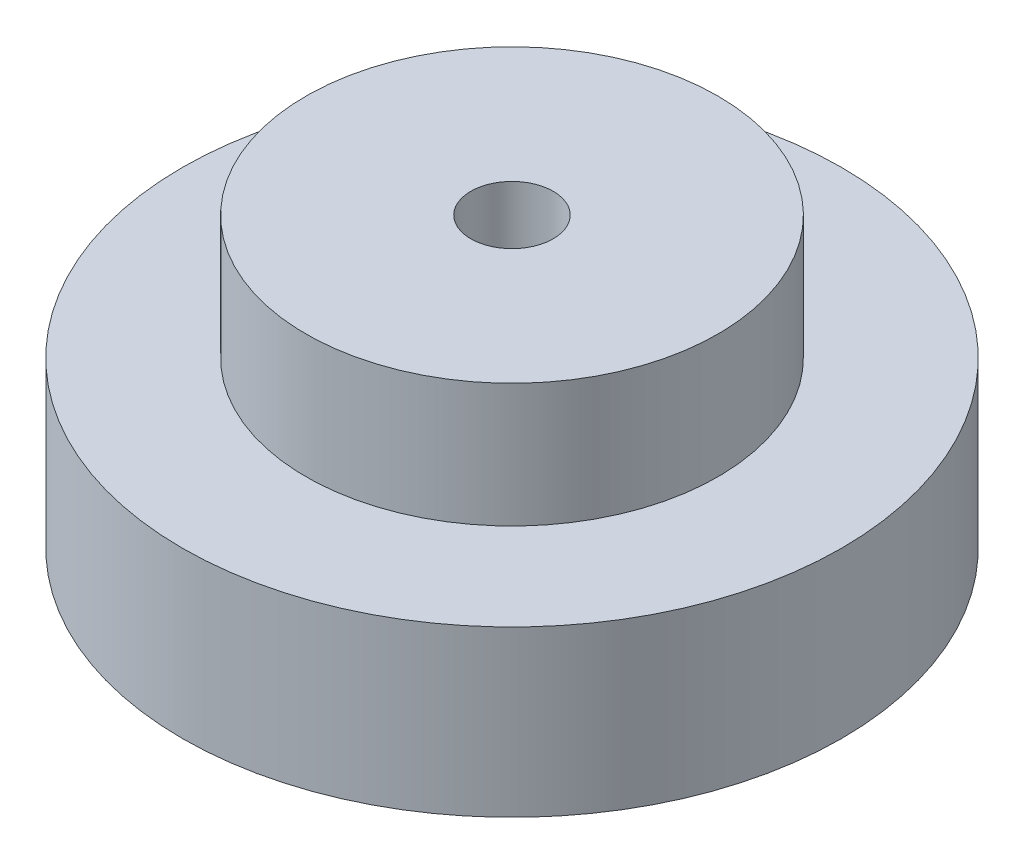
SolidWorks part; units mm, degrees
ref_plane "前视基准面" through (0, 0, 0) normal (0, 0, 1) x (1, 0, 0)
ref_plane "上视基准面" through (0, 0, 0) normal (0, 1, 0) x (1, 0, 0)
ref_plane "右视基准面" through (0, 0, 0) normal (1, 0, 0) x (0, 0, -1)
sketch "草图1" plane through (0, 0, 0) normal (0, 0, 1) x (1, 0, 0)
  line L1 (10, 30) -> (50, 30)
  line L2 (50, 30) -> (50, 0)
  line L3 (33.1915, -40) -> (15, -40)
  line L4 (0, -30) -> (0, 0)
  line L5 (50, 0) -> (80, 0)
  line L6 (80, 0) -> (80, -40)
  line L7 (80, -40) -> (33.1915, -40)
  line L8 (10, 30) -> (10, 0)
  line L9 (10, 0) -> (0, 0)
  line L10 (0, -30) -> (15, -30)
  line L11 (15, -30) -> (15, -40)
  dimension "D1" = 15
  dimension "D2" = 30
  dimension "D3" = 30
  dimension "D4" = 40
  dimension "D6" = 30
revolve "旋转1" add sketch "草图1" angle 360 about L4
hole_wizard "M6 螺纹孔2" positions "草图4" profile "草图5" tap size "M6" standard "GB" end condition through all
sketch "草图4" plane through (0, -30, 0) normal (0, -1, 0) x (-1, 0, 0)
  point P0 (0, 0)
sketch "草图5" plane through (0, -30, 0) normal (1, 0, 0) x (0, 0, -1)
  line L0 (0, 0) -> (0, 60)
  line L1 (0, 60) -> (2.5, 60)
  line L2 (2.5, 60) -> (2.5, 0)
  line L5 (2.5, 0) -> (0, 0)
  line L11 (0, -6.35) -> (0, 107.95) construction
  dimension "通孔螺纹孔钻头直径" = 5
  dimension "通孔螺纹孔钻头深度" = 60
cosmetic thread "孔螺蚊线2" parameters "D2"=6
